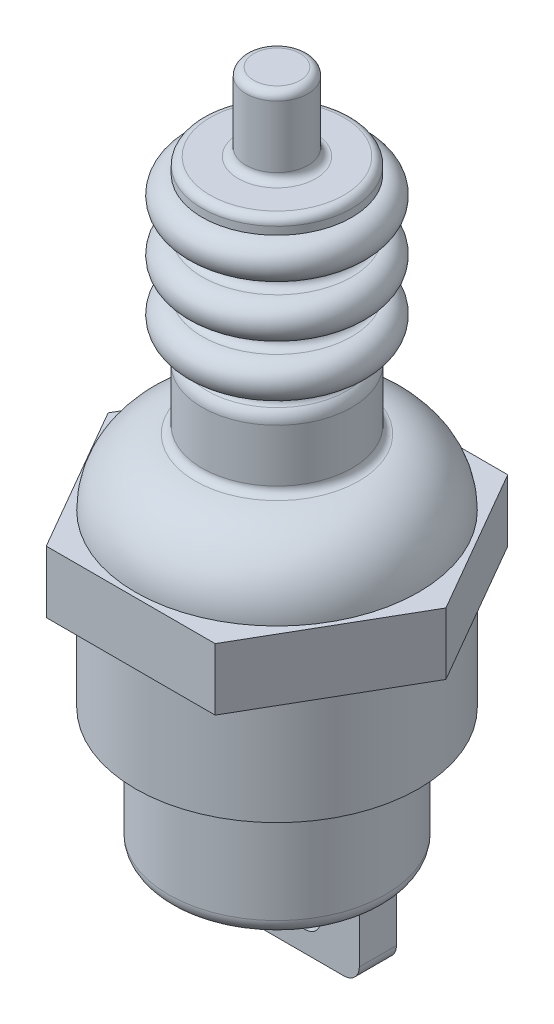
SolidWorks part; units mm, degrees
ref_plane "Front Plane" through (0, 0, 0) normal (0, 0, 1) x (1, 0, 0)
ref_plane "Top Plane" through (0, 0, 0) normal (0, 1, 0) x (1, 0, 0)
ref_plane "Right Plane" through (0, 0, 0) normal (1, 0, 0) x (0, 0, -1)
sketch "Sketch1" plane through (0, 0, 0) normal (0, 0, 1) x (1, 0, 0)
  line L1 (0, 52.1369) -> (-2, 52.1369)
  line L2 (-2, 52.1369) -> (-2, 47.1369)
  line L3 (-2, 47.1369) -> (-4.8333, 47.1369)
  line L4 (-4.8333, 47.1369) -> (-4.8333, 46.1369)
  line L5 (-7, 16.3282) -> (-7, 9.3282)
  line L6 (-4.8333, 46.1369) -> (-4.8333, 43.8035) construction
  line L7 (-4.8333, 43.8035) -> (-4.8333, 43.3035) construction
  line L8 (-4.8333, 43.3035) -> (-4.8333, 42.8035) construction
  line L9 (-1.6, 8.3282) -> (-1.1, 8.3282)
  line L10 (-1.1, 8.3282) -> (-1.1, 7.5589)
  line L11 (-9.15, 27.3282) -> (-4.8413, 27.3282) construction
  line L12 (-9.15, 27.3282) -> (-9.15, 16.3282)
  line L13 (-9.15, 16.3282) -> (0, 16.3282) construction
  line L14 (-9.15, 16.3282) -> (-7, 16.3282)
  line L15 (-0.6, 7.0589) -> (0, 7.0589)
  line L16 (-6, 8.3282) -> (-5, 8.3282)
  line L17 (-4.5, 8.8282) -> (-4.5, 10.0613)
  line L18 (-3.5, 11.0613) -> (-3.1, 11.0613)
  line L19 (-2.1, 10.0613) -> (-2.1, 8.8282)
  line L21 (0, 7.0589) -> (0, 52.1369)
  line L22 (-4.8413, 35.5117) -> (-4.8413, 32.1108)
  arc A0 (-4.8333, 46.1369) -> (-4.8333, 43.8035) centre (-4.8333, 44.9702) ccw
  arc A1 (-4.8333, 42.8035) -> (-4.8333, 43.8035) centre (-4.8333, 43.3035) ccw
  arc A2 (-5.2893, 31.6135) -> (-9.15, 27.3282) centre (-4.8413, 27.3282) ccw
  arc A3 (-4.8333, 42.8035) -> (-4.8333, 40.4702) centre (-4.8333, 41.6369) ccw
  arc A4 (-4.8333, 39.4702) -> (-4.8333, 40.4702) centre (-4.8333, 39.9702) ccw
  arc A5 (-4.8333, 39.4702) -> (-4.8333, 37.1368) centre (-4.8333, 38.3035) ccw
  arc A6 (-4.5026, 36.2618) -> (-4.8333, 37.1368) centre (-4.8333, 36.6368) ccw
  arc A7 (-4.5026, 36.2618) -> (-4.8413, 35.5117) centre (-3.8413, 35.5117) ccw
  arc A8 (-3.1, 11.0613) -> (-2.1, 10.0613) centre (-3.1, 10.0613) cw
  arc A9 (-4.8333, 36.1368) -> (-4.8333, 33.8035) centre (-4.8333, 34.9702) ccw [skipped]
  arc A10 (-4.8333, 32.8035) -> (-4.8333, 33.8035) centre (-4.8333, 33.3035) ccw [skipped]
  arc A11 (-4.5, 10.0613) -> (-3.5, 11.0613) centre (-3.5, 10.0613) cw
  arc A12 (-7, 9.3282) -> (-6, 8.3282) centre (-6, 9.3282) ccw
  arc A13 (-2.1, 8.8282) -> (-1.6, 8.3282) centre (-1.6, 8.8282) ccw
  arc A14 (-1.1, 7.5589) -> (-0.6, 7.0589) centre (-0.6, 7.5589) ccw
  arc A15 (-5, 8.3282) -> (-4.5, 8.8282) centre (-5, 8.8282) ccw
  arc A16 (-4.8413, 32.1108) -> (-5.2893, 31.6135) centre (-5.3413, 32.1108) cw
  point P27 (-4.8413, 36.1369)
  point P52 (-7, 8.3282)
  point P55 (-2.1, 8.3282)
  point P58 (-1.1, 7.0589)
  point P61 (-4.5, 8.3282)
  point P64 (-4.8413, 31.6369)
  dimension "D1" = 2
  dimension "D9" = 1
  dimension "D17" = 1
  dimension "D18" = 0.5
  dimension "D19" = 0.5
  dimension "D20" = 0.5
  dimension "D2" = 5
  dimension "D3" = 1
  dimension "D4" = 11
  dimension "D5" = 3.4009
  dimension "D7" = 10
  dimension "D8" = 4.5
  dimension "D11" = 0.5
  dimension "D13" = 8
  dimension "D14" = 2.5
  dimension "D15" = 1
  dimension "D16" = 1.1
  dimension "D6" = 4
revolve "Revolve2" add sketch "Sketch1" angle 360 about L21
ref_plane "Plane1" through (0, 23.3282, 0) normal (0, -1, 0) x (-1, 0, 0)
sketch "Sketch2" plane through (0, 23.3282, 0) normal (0, -1, 0) x (-1, 0, 0)
  line L1 (10.9119, 0) -> (5.456, 9.45)
  line L2 (5.456, 9.45) -> (-5.456, 9.45)
  line L3 (-5.456, 9.45) -> (-10.9119, 0)
  line L4 (-10.9119, 0) -> (-5.456, -9.45)
  line L5 (-5.456, -9.45) -> (5.456, -9.45)
  line L6 (5.456, -9.45) -> (10.9119, 0)
  circle A0 centre (0, 0) radius 9.45 construction
  dimension "D1" = 18.9
extrude "Boss-Extrude1" add sketch "Sketch2" against normal blind 4
fillet "Fillet1" radius 0.5 3 edges at (4.8333, 47.1369, 0) (2, 47.1369, 0) (2, 52.1369, 0)
sketch "Sketch3" plane through (0, 0, 0) normal (0, 0, 1) x (1, 0, 0)
  line L0 (6.5169, 5.6459) -> (6.5169, 9.2307)
  line L1 (5.5169, 4.6459) -> (-2.2342, 4.6459)
  line L2 (-2.2342, 4.6459) -> (-2.2342, 5.9917)
  line L3 (-2.2342, 5.9917) -> (3.0151, 5.9917)
  line L7 (4.0151, 6.9917) -> (4.0151, 9.2307)
  line L8 (4.0151, 9.2307) -> (6.5169, 9.2307)
  arc A0 (3.0151, 5.9917) -> (4.0151, 6.9917) centre (3.0151, 6.9917) ccw
  arc A1 (5.5169, 4.6459) -> (6.5169, 5.6459) centre (5.5169, 5.6459) ccw
  dimension "D1" = 1
extrude "Boss-Extrude2" add sketch "Sketch3" along normal blind 1.2 and the other way blind 1.2
